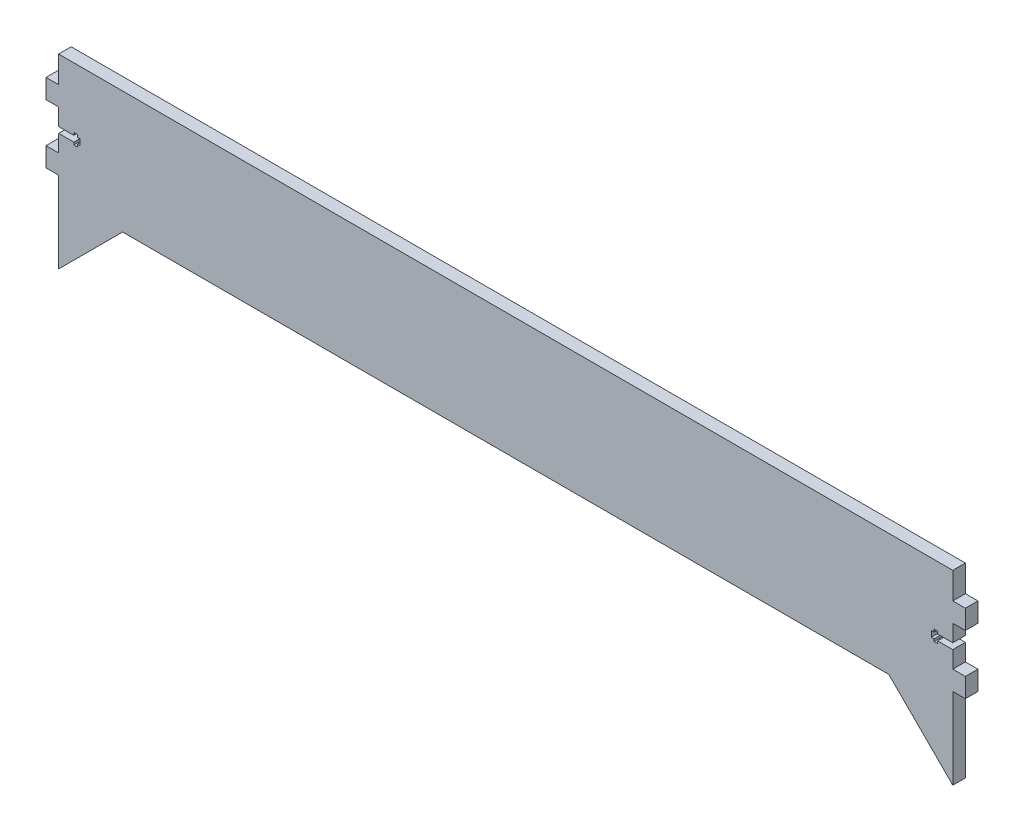
SolidWorks part; units mm, degrees
material "Acrylic (Medium-high impact)"
ref_plane "Front Plane" through (0, 0, 0) normal (0, 0, 1) x (1, 0, 0)
ref_plane "Top Plane" through (0, 0, 0) normal (0, 1, 0) x (1, 0, 0)
ref_plane "Right Plane" through (0, 0, 0) normal (1, 0, 0) x (0, 0, -1)
sketch "Sketch1" plane through (0, 0, 0) normal (0, 0, 1) x (1, 0, 0)
  line L0 (-194.226, 22.243) -> (194.7837, 22.243)
  line L1 (-194.226, 22.243) -> (-226.7211, -10.2522)
  line L2 (-111.7211, 199.2478) -> (-226.7211, 84.2478) construction
  line L3 (97.2789, 199.2478) -> (112.2789, 199.2478) construction
  line L4 (227.2789, 49.3771) -> (227.2789, 40.7778)
  line L5 (112.2789, 199.2478) -> (227.2789, 84.2478) construction
  line L6 (-226.7211, 84.2478) -> (-226.7211, 70.7778)
  line L7 (-96.7211, 199.2478) -> (-111.7211, 199.2478) construction
  line L8 (-226.7211, 84.2478) -> (227.2789, 84.2478)
  line L9 (-219.0211, 49.3771) -> (-226.7211, 49.3771)
  line L10 (-226.7211, 60.9778) -> (-226.7211, 52.3785)
  line L11 (-233.1211, 40.7778) -> (-233.1211, 30.9778)
  line L12 (-217.2211, 48.1285) -> (-217.2211, 49.3771)
  line L13 (15.2795, 193.6478) -> (15.2795, 187.2478) construction
  line L14 (-14.7218, 193.6478) -> (-14.7218, 187.2478) construction
  line L15 (-19.6218, 187.2478) -> (-9.8218, 187.2478) construction
  line L16 (10.3795, 187.2478) -> (10.3795, 193.6478) construction
  line L17 (-19.6218, 193.6478) -> (-9.8218, 193.6478) construction
  line L18 (20.1795, 187.2478) -> (20.1795, 193.6478) construction
  line L19 (-9.8218, 190.4478) -> (10.3795, 190.4478) construction
  line L20 (-19.6218, 187.2478) -> (-19.6218, 193.6478) construction
  line L21 (-9.8218, 187.2478) -> (-9.8218, 193.6478) construction
  line L22 (20.1795, 193.6478) -> (10.3795, 193.6478) construction
  line L23 (20.1795, 187.2478) -> (10.3795, 187.2478) construction
  line L24 (-215.8211, 49.3771) -> (-217.2211, 49.3771)
  line L25 (-217.2211, 52.3785) -> (-217.2211, 53.6285)
  line L26 (-226.7211, 30.9778) -> (-226.7211, -10.2522)
  line L27 (-217.2211, 53.6285) -> (-219.0211, 53.6285)
  line L28 (-215.8211, 52.3785) -> (-217.2211, 52.3785)
  line L29 (-219.0211, 52.3785) -> (-226.7211, 52.3785)
  line L30 (-226.7211, 40.7778) -> (-233.1211, 40.7778)
  line L31 (-219.0211, 53.6285) -> (-219.0211, 52.3785)
  line L32 (-233.1211, 30.9778) -> (-226.7211, 30.9778)
  line L33 (-226.7211, 70.7778) -> (-233.1211, 70.7778)
  line L34 (-233.1211, 70.7778) -> (-233.1211, 60.9778)
  line L35 (194.7837, 22.243) -> (227.2789, -10.2522)
  line L36 (-219.0211, 48.1285) -> (-219.0211, 49.3771)
  line L37 (-96.7211, 199.2478) -> (97.2789, 199.2478) construction
  line L38 (-233.1211, 60.9778) -> (-226.7211, 60.9778)
  line L39 (-217.2211, 48.1285) -> (-219.0211, 48.1285)
  line L40 (-215.8211, 52.3785) -> (-215.8211, 49.3771)
  line L41 (-226.7211, 49.3771) -> (-226.7211, 40.7778)
  line L42 (216.3789, 52.3785) -> (216.3789, 49.3771)
  line L43 (217.7789, 48.1285) -> (219.5789, 48.1285)
  line L44 (233.6789, 60.9778) -> (227.2789, 60.9778)
  line L45 (219.5789, 48.1285) -> (219.5789, 49.3771)
  line L46 (233.6789, 70.7778) -> (233.6789, 60.9778)
  line L47 (227.2789, 70.7778) -> (233.6789, 70.7778)
  line L48 (233.6789, 30.9778) -> (227.2789, 30.9778)
  line L49 (219.5789, 53.6285) -> (219.5789, 52.3785)
  line L50 (227.2789, 40.7778) -> (233.6789, 40.7778)
  line L51 (219.5789, 52.3785) -> (227.2789, 52.3785)
  line L52 (216.3789, 52.3785) -> (217.7789, 52.3785)
  line L53 (217.7789, 53.6285) -> (219.5789, 53.6285)
  line L54 (227.2789, 30.9778) -> (227.2789, -10.2522)
  line L55 (217.7789, 52.3785) -> (217.7789, 53.6285)
  line L56 (216.3789, 49.3771) -> (217.7789, 49.3771)
  line L57 (217.7789, 48.1285) -> (217.7789, 49.3771)
  line L58 (233.6789, 40.7778) -> (233.6789, 30.9778)
  line L59 (227.2789, 60.9778) -> (227.2789, 52.3785)
  line L60 (219.5789, 49.3771) -> (227.2789, 49.3771)
  line L61 (227.2789, 84.2478) -> (227.2789, 70.7778)
  line L75 (0.2789, 199.2478) -> (0.2789, 190.4478) construction
  circle A1 centre (0.2789, 190.4478) radius 1.5 construction
  dimension "D1" = 15
  dimension "D2" = 8.8
extrude "Boss-Extrude1" add sketch "Sketch1" along normal blind 6.4
